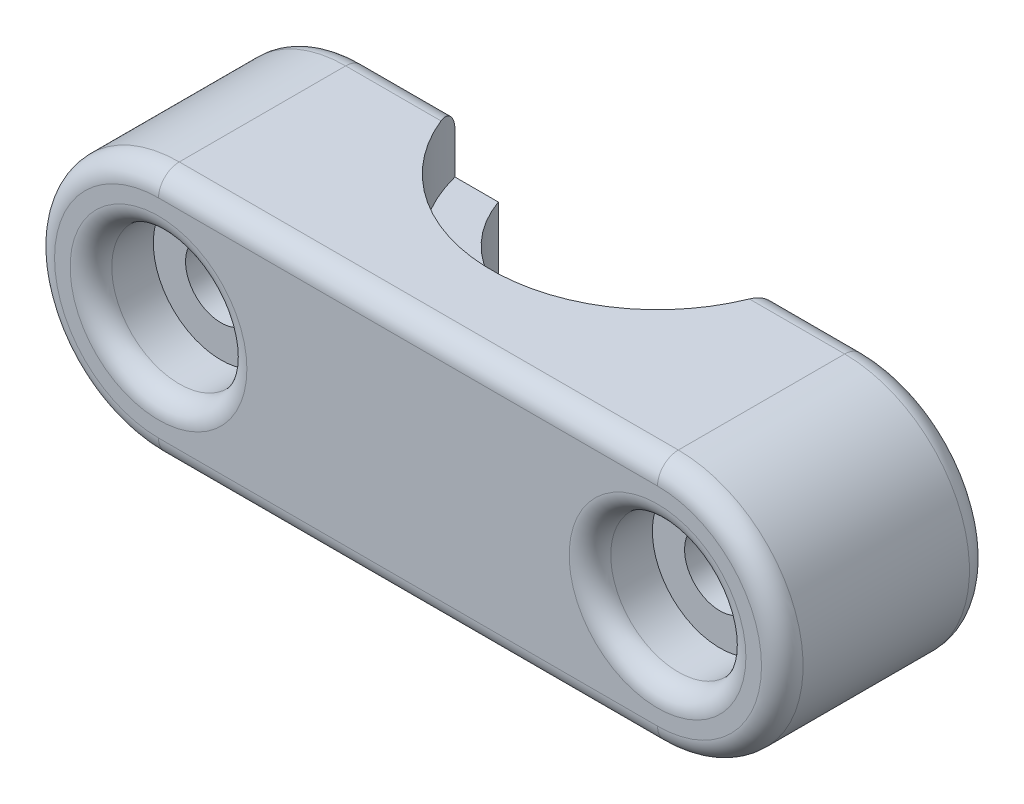
SolidWorks part; units mm, degrees
ref_plane "Front Plane" through (0, 0, 0) normal (0, 0, 1) x (1, 0, 0)
ref_plane "Top Plane" through (0, 0, 0) normal (0, 1, 0) x (1, 0, 0)
ref_plane "Right Plane" through (0, 0, 0) normal (1, 0, 0) x (0, 0, -1)
sketch "Sketch1" plane through (0, 0, 0) normal (0, 0, 1) x (1, 0, 0)
  line L0 (-12, 0) -> (12, 0) construction
  line L1 (-12, 6) -> (12, 6)
  line L2 (-12, -6) -> (12, -6)
  arc A0 (-12, 6) -> (-12, -6) centre (-12, 0) ccw
  arc A1 (12, -6) -> (12, 6) centre (12, 0) ccw
  point P2 (0, 0)
  dimension "D1" = 12
  dimension "D2" = 24
extrude "Boss-Extrude1" add sketch "Sketch1" along normal blind 10 from offset 2
hole_wizard "CBORE for M3 SHCS2" positions "Sketch11" profile "Sketch10" counterbore size "M3" standard "ANSI Metric" end condition through all
sketch "Sketch11" plane through (0, 0, 12) normal (0, 0, 1) x (1, 0, 0)
  arc A0 (-12, 6) -> (-12, -6) centre (-12, 0) ccw construction
  arc A1 (12, -6) -> (12, 6) centre (12, 0) ccw construction
  point P0 (-12, 0)
  point P2 (12, 0)
sketch "Sketch10" plane through (-12, 0, 12) normal (1, 0, 0) x (0, -1, 0)
  line L0 (0, 0) -> (0, 10)
  line L1 (0, 10) -> (1.7, 10)
  line L3 (1.7, 10) -> (1.7, 3)
  line L4 (1.7, 3) -> (3.25, 3)
  line L5 (3.25, 3) -> (3.25, 0)
  line L7 (3.25, 0) -> (0, 0)
  line L11 (0, -6.35) -> (0, 107.95) construction
  dimension "Thru Hole Dia." = 3.4
  dimension "Thru Hole Depth" = 10
  dimension "C'Bore Dia." = 6.5
  dimension "C'Bore Depth" = 3
fillet "Fillet1" radius 1 10 edges at (0, 6, 12) (18, 0, 12) (0, -6, 12) (-18, 0, 12) (15.25, 0, 12) (-8.75, 0, 12) (0, -6, 2) (-18, 0, 2) (18, 0, 2) (0, 6, 2)
sketch "Sketch13" plane through (0, 0, 0) normal (1, 0, 0) x (0, 0, -1)
  line L0 (0, 6) -> (0, -6)
  line L1 (0, -6) -> (8, -6)
  line L2 (8, -6) -> (8, -3)
  line L3 (8, -3) -> (6, -3)
  line L4 (6, -3) -> (6, 3)
  line L5 (6, 3) -> (8, 3)
  line L6 (8, 3) -> (8, 6)
  line L7 (8, 6) -> (0, 6)
  line L8 (0, 6) -> (0, -6) construction
  dimension "D1" = 8
  dimension "D2" = 6
  dimension "D3" = 3
  dimension "D4" = 6
  dimension "D5" = 3
revolve "Cut-Revolve1" cut sketch "Sketch13" angle 360 about L0
